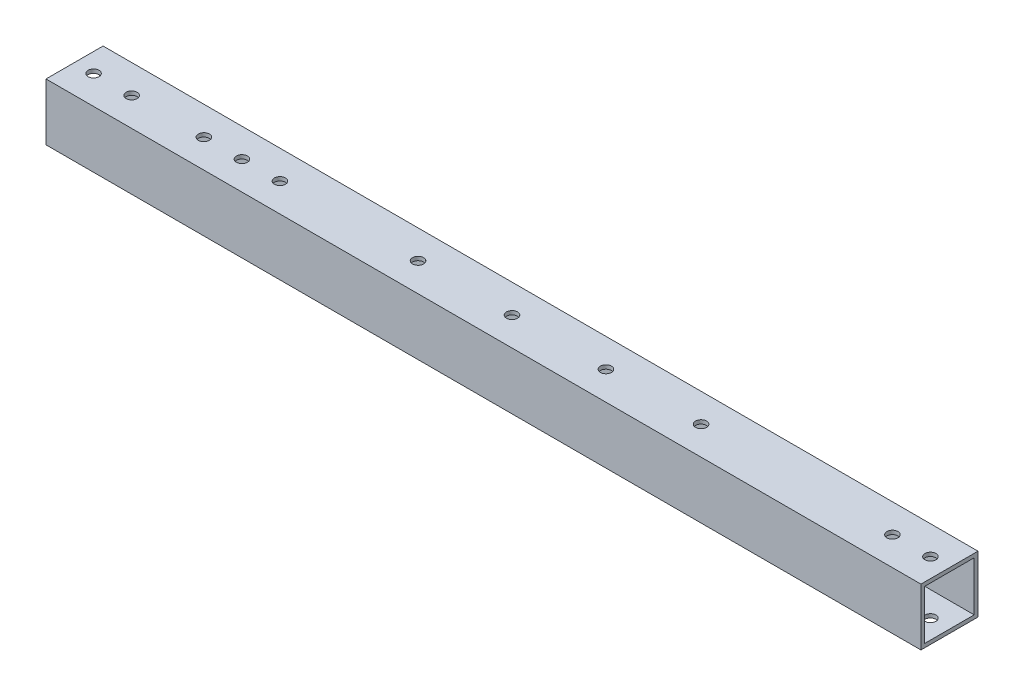
SolidWorks part; units mm, degrees
material "Thornel Mat VMA"
ref_plane "前视基准面" through (0, 0, 0) normal (0, 0, 1) x (1, 0, 0)
ref_plane "上视基准面" through (0, 0, 0) normal (0, 1, 0) x (1, 0, 0)
ref_plane "右视基准面" through (0, 0, 0) normal (1, 0, 0) x (0, 0, -1)
other "Configuration Table"
sketch "草图1" plane through (0, 0, 0) normal (1, 0, 0) x (0, 0, -1)
  line L0 (-6.5, -6.5) -> (-6.5, 6.5)
  line L1 (-7.5, -7.5) -> (7.5, -7.5)
  line L2 (-7.5, -7.5) -> (-7.5, 7.5)
  line L3 (-7.5, 7.5) -> (7.5, 7.5)
  line L4 (7.5, -7.5) -> (7.5, 7.5)
  line L5 (-7.5, -7.5) -> (7.5, 7.5) construction
  line L6 (-7.5, 7.5) -> (7.5, -7.5) construction
  line L7 (-6.5, 6.5) -> (6.5, 6.5)
  line L8 (6.5, -6.5) -> (6.5, 6.5)
  line L9 (-6.5, -6.5) -> (6.5, -6.5)
  point P0 (0, 0)
  dimension "D1" = 15
  dimension "D2" = 15
  dimension "D3" = 1
extrude "凸台-拉伸1" add sketch "草图1" along normal blind 230
sketch "草图2" plane through (0, -7.5, 0) normal (0, -1, 0) x (1, 0, 0)
  line L0 (-9.6535, 0) -> (150.5273, 0) construction
  circle A0 centre (215, 0) radius 1.45 construction
  circle A1 centre (225, 0) radius 1.45 construction
  circle A2 centre (164.6985, 0) radius 1.45 construction
  circle A3 centre (139.6985, 0) radius 1.45 construction
  circle A4 centre (5, 0) radius 1.45 construction
  circle A5 centre (15, 0) radius 1.45 construction
  circle A6 centre (215, 0) radius 1.45
  circle A7 centre (225, 0) radius 1.45
  circle A8 centre (164.6985, 0) radius 1.45
  circle A9 centre (139.6985, 0) radius 1.45
  circle A10 centre (5, 0) radius 1.45
  circle A11 centre (15, 0) radius 1.45
  circle A12 centre (115, 0) radius 1.45 construction
  circle A13 centre (90.3, 0) radius 1.45 construction
  circle A14 centre (115, 0) radius 1.45
  circle A15 centre (90.3, 0) radius 1.45
  circle A16 centre (34, 0) radius 1.45
  circle A17 centre (44, 0) radius 1.45
  circle A18 centre (54, 0) radius 1.45
  dimension "D1" = 19
  dimension "D2" = 10
  dimension "D3" = 10
extrude "切除-拉伸1" cut sketch "草图2" against normal through all
